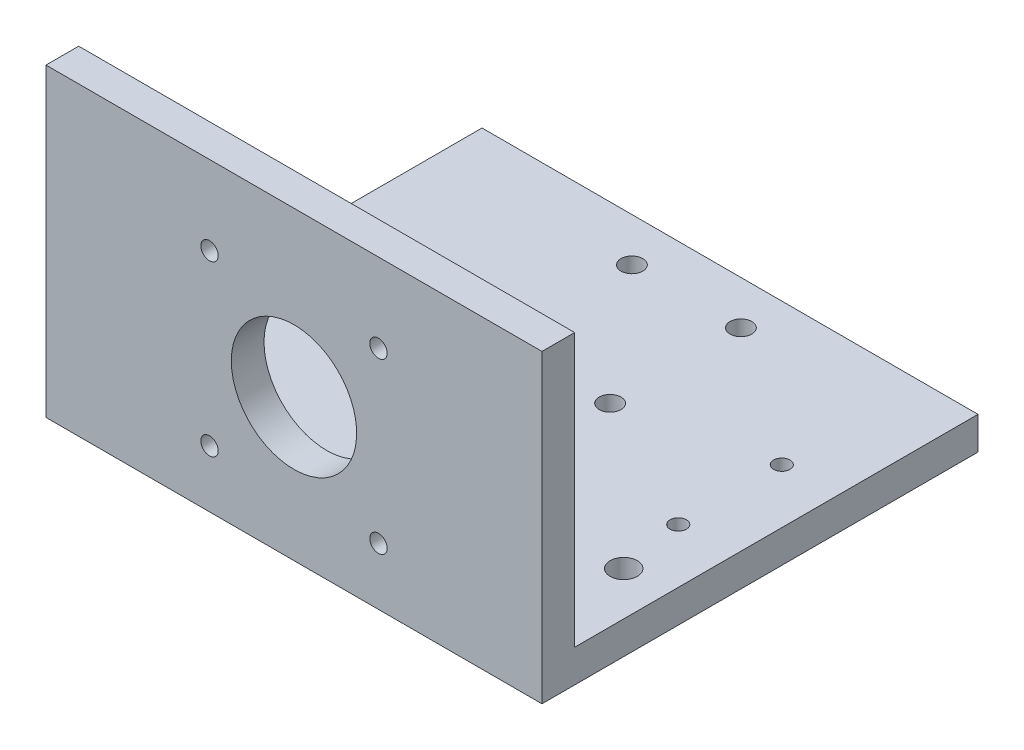
SolidWorks part; units mm, degrees
ref_plane "前视基准面" through (0, 0, 0) normal (0, 0, 1) x (1, 0, 0)
ref_plane "上视基准面" through (0, 0, 0) normal (0, 1, 0) x (1, 0, 0)
ref_plane "右视基准面" through (0, 0, 0) normal (1, 0, 0) x (0, 0, -1)
sketch "草图1" plane through (0, 0, 0) normal (1, 0, 0) x (0, 0, -1)
  line L0 (6, 6) -> (0, 6) construction
  line L1 (0, 0) -> (80, 0)
  line L2 (0, 0) -> (0, 6)
  line L3 (6, 6) -> (80, 6)
  line L4 (80, 0) -> (80, 6)
  line L6 (0, 6) -> (0, 80)
  line L7 (0, 80) -> (6, 80)
  line L8 (6, 6) -> (6, 80)
  dimension "D1" = 6
  dimension "D2" = 80
  dimension "D3" = 6
  dimension "D4" = 74
extrude "凸台-拉伸1" add sketch "草图1" along normal blind 104
sketch "草图2" plane through (0, 6, 0) normal (0, 1, 0) x (1, 0, 0)
  line L0 (104, 6) -> (0, 6) construction
  line L1 (52, 6) -> (52, 80) construction
  line L2 (104, 80) -> (0, 80) construction
  line L3 (61, 11) -> (61, 35) construction
  line L4 (104, 23) -> (0, 23) construction
  line L5 (104, 80) -> (104, 6) construction
  line L6 (0, 80) -> (0, 6) construction
  line L7 (97.5, 6) -> (97.5, 80)
  line L8 (97.5, 6) -> (104, 6)
  line L9 (104, 6) -> (104, 80)
  line L10 (104, 80) -> (97.5, 80)
  line L11 (0, 6) -> (0, 80)
  line L12 (6.5, 6) -> (0, 6)
  line L13 (6.5, 6) -> (6.5, 80)
  line L14 (0, 80) -> (6.5, 80)
  circle A0 centre (43, 11) radius 2
  circle A1 centre (43, 35) radius 2
  circle A2 centre (42, 48) radius 2
  circle A3 centre (42, 72) radius 2
  circle A4 centre (62, 72) radius 2
  circle A5 centre (62, 48) radius 2
  circle A6 centre (61, 35) radius 2
  circle A7 centre (61, 11) radius 2
  circle A8 centre (57.5, 23) radius 2.5
  circle A9 centre (89.5, 23) radius 2.5
  circle A10 centre (46.5, 23) radius 2.5
  circle A11 centre (14.5, 23) radius 2.5
  circle A15 centre (87.5, 35) radius 1.5
  circle A16 centre (87.5, 54) radius 1.5
  dimension "D1" = 24
  dimension "D4" = 24
  dimension "D8" = 32
  dimension "D7" = 5.5
  dimension "D2" = 5
  dimension "D3" = 9
  dimension "D5" = 10
  dimension "D6" = 8
  dimension "D10" = 8
extrude "切除-拉伸1" cut sketch "草图2" against normal through all
sketch "草图3" plane through (0, 0, -6) normal (0, 0, -1) x (-1, 0, 0)
  line L0 (-97.5, 6) -> (-6.5, 6) construction
  line L1 (-52, 6) -> (-52, 80) construction
  line L2 (-104, 80) -> (0, 80) construction
  line L3 (-34.043, 26) -> (-70.2707, 26) construction
  line L4 (-97.5, 0) -> (-97.5, 56)
  line L6 (-104, 80) -> (-104, 0)
  line L7 (-104, 0) -> (-97.5, 0)
  line L8 (-97.5, 56) -> (-6.5, 56)
  line L9 (-104, 80) -> (0, 80)
  line L10 (-97.5, 6) -> (-6.5, 6) construction
  line L11 (-6.5, 0) -> (-6.5, 56)
  line L12 (0, 0) -> (-6.5, 0)
  line L13 (0, 80) -> (0, 0)
  circle A0 centre (-52, 26) radius 11.5
  circle A1 centre (-36.5, 41.5) radius 1.6
  circle A3 centre (-67.5, 41.5) radius 1.6
  circle A4 centre (-67.5, 10.5) radius 1.6
  circle A5 centre (-36.5, 10.5) radius 1.6
  point P29 (-52, 56)
  dimension "D1" = 20
  dimension "D2" = 15.5
  dimension "D3" = 15.5
  dimension "D4" = 50
extrude "切除-拉伸2" cut sketch "草图3" against normal through all
